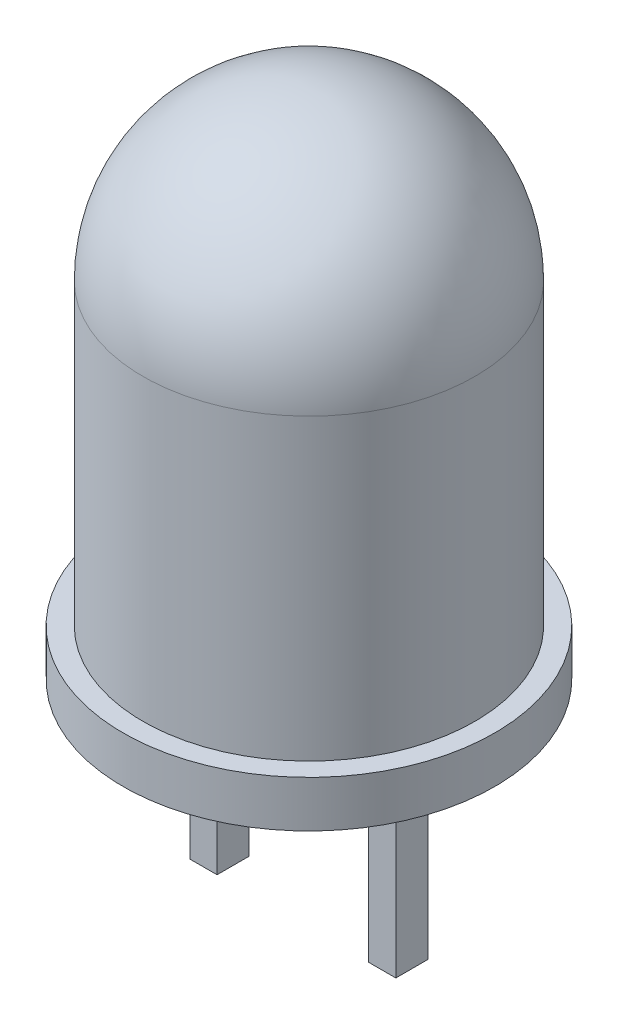
SolidWorks part; units mm, degrees
ref_plane "Front Plane" through (0, 0, 0) normal (0, 0, 1) x (1, 0, 0)
ref_plane "Top Plane" through (0, 0, 0) normal (0, 1, 0) x (1, 0, 0)
ref_plane "Right Plane" through (0, 0, 0) normal (1, 0, 0) x (0, 0, -1)
sketch "Sketch2" plane through (0, 0, 0) normal (0, 1, 0) x (1, 0, 0)
  circle A0 centre (0, 0) radius 2.5
  dimension "D1" = 5
extrude "Boss-Extrude1" add sketch "Sketch2" along normal blind 7
sketch "Sketch3" plane through (0, 0, 0) normal (0, -1, 0) x (1, 0, 0)
  circle A0 centre (0, 0) radius 2.8
extrude "Boss-Extrude2" add sketch "Sketch3" along normal blind 0.7
fillet "Fillet1" radius 2.5 1 edges at (0, 7, 2.5)
sketch "Sketch4" plane through (0, -0.7, 0) normal (0, -1, 0) x (1, 0, 0)
  line L0 (0, 1.6752) -> (0, -2.0522) construction
  line L1 (1.1419, -0.2424) -> (1.5513, -0.2424)
  line L2 (1.1419, -0.2424) -> (1.1419, 0.2424)
  line L3 (1.1419, 0.2424) -> (1.5513, 0.2424)
  line L4 (1.5513, -0.2424) -> (1.5513, 0.2424)
  line L5 (1.1419, -0.2424) -> (1.5513, 0.2424) construction
  line L6 (1.1419, 0.2424) -> (1.5513, -0.2424) construction
  line L7 (-1.1419, 0.2424) -> (-1.5513, -0.2424) construction
  line L8 (-1.1419, -0.2424) -> (-1.5513, 0.2424) construction
  line L9 (-1.5513, -0.2424) -> (-1.5513, 0.2424)
  line L10 (-1.1419, 0.2424) -> (-1.5513, 0.2424)
  line L11 (-1.1419, -0.2424) -> (-1.1419, 0.2424)
  line L12 (-1.1419, -0.2424) -> (-1.5513, -0.2424)
  point P0 (1.3466, 0)
  point P12 (-1.3466, 0)
extrude "Boss-Extrude3" add sketch "Sketch4" along normal blind 3
